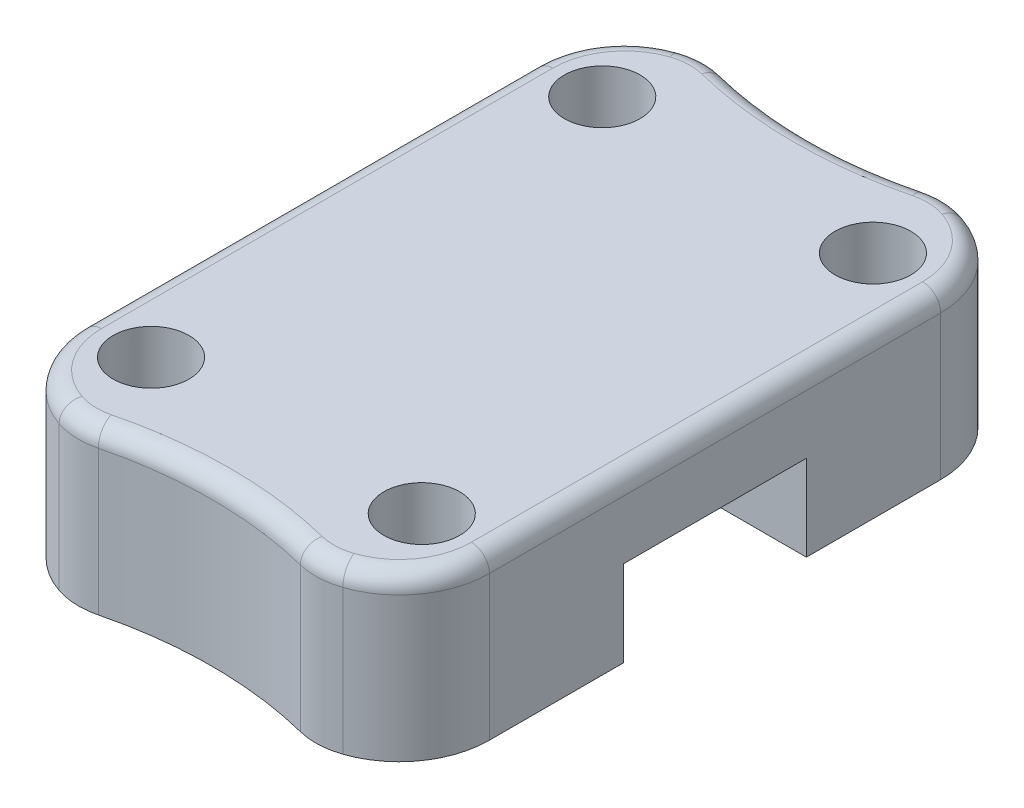
SolidWorks part; units mm, degrees
ref_plane "Спереди" through (0, 0, 0) normal (0, 0, 1) x (1, 0, 0)
ref_plane "Сверху" through (0, 0, 0) normal (0, 1, 0) x (1, 0, 0)
ref_plane "Справа" through (0, 0, 0) normal (1, 0, 0) x (0, 0, -1)
sketch "Sketch1" plane through (0, 0, 0) normal (0, 1, 0) x (1, 0, 0)
  line L1 (22.5, -35) -> (-22.5, -35)
  line L2 (22.5, -35) -> (22.5, 35)
  line L3 (22.5, 35) -> (-22.5, 35)
  line L4 (-22.5, -35) -> (-22.5, 35)
  line L5 (22.5, -35) -> (-22.5, 35) construction
  line L6 (22.5, 35) -> (-22.5, -35) construction
  point P0 (0, 0)
  dimension "D1" = 45
  dimension "D2" = 70
extrude "Boss-Extrude1" add sketch "Sketch1" along normal blind 18
sketch "Sketch2" plane through (22.5, 0, 0) normal (1, 0, 0) x (0, 0, -1)
  line L0 (0, 0) -> (0, 18) construction
  line L1 (-35, 0) -> (35, 0) construction
  line L2 (-35, 18) -> (35, 18) construction
  line L4 (10.125, 9.5) -> (-10.125, 9.5)
  line L5 (10.125, 9.5) -> (10.125, 0)
  line L6 (10.125, 0) -> (-10.125, 0)
  line L7 (-10.125, 9.5) -> (-10.125, 0)
  line L8 (10.125, 9.5) -> (-10.125, 0) construction
  line L9 (10.125, 0) -> (-10.125, 9.5) construction
  point P6 (0, 4.75)
  dimension "D1" = 20.25
  dimension "D2" = 9.5
extrude "Cut-Extrude1" cut sketch "Sketch2" against normal through all and the other way through all
sketch "Sketch3" plane through (0, 0, 0) normal (0, -1, 0) x (1, 0, 0)
  line L0 (15, -25) -> (15, 25) construction
  line L1 (-15, 25) -> (-15, -25) construction
  line L2 (-15, -25) -> (15, 25) construction
  line L3 (-22.5, -25) -> (22.5, -25) construction
  line L4 (-22.5, -35) -> (-22.5, -10.125) construction
  line L5 (22.5, -10.125) -> (22.5, -35) construction
  line L6 (-22.5, 25) -> (22.5, 25) construction
  line L7 (-22.5, 10.125) -> (-22.5, 35) construction
  line L8 (22.5, 35) -> (22.5, 10.125) construction
  line L9 (-15, 25) -> (15, -25) construction
  circle A0 centre (15, 25) radius 4.2
  circle A1 centre (15, -25) radius 4.2
  circle A2 centre (-15, -25) radius 4.2
  circle A3 centre (-15, 25) radius 4.2
  point P4 (0, 0)
  dimension "D1" = 8.4
  dimension "D2" = 30
  dimension "D3" = 50
extrude "Cut-Extrude2" cut sketch "Sketch3" against normal through all
fillet "Fillet1" radius 10 4 edges at (-22.5, 9, 35) (22.5, 9, 35) (-22.5, 9, -35) (22.5, 9, -35)
sketch "Sketch6" plane through (0, 0, 0) normal (0, -1, 0) x (1, 0, 0)
  line L0 (12.5, 35) -> (-12.5, 35)
  line L1 (12.5, -35) -> (-12.5, -35)
  arc A0 (12.5, -35) -> (-12.5, -35) centre (0, -79.2691) ccw
  arc A1 (12.5, 35) -> (-12.5, 35) centre (0, 79.2691) cw
  dimension "D1" = 46
extrude "Cut-Extrude3" cut sketch "Sketch6" against normal through all
fillet "Fillet2" radius 8 4 edges at (-12.5, 9, -35) (12.5, 9, -35) (12.5, 9, 35) (-12.5, 9, 35)
fillet "Fillet4" radius 2 12 edges at (-20.631, 18, -30.8212) (-13.4734, 18, -34.8865) (0, 18, -33.2691) (13.4734, 18, -34.8865) (20.631, 18, -30.8212) (22.5, 18, 0) (20.631, 18, 30.8212) (13.4734, 18, 34.8865) (0, 18, 33.2691) (-13.4734, 18, 34.8865) (-20.631, 18, 30.8212) (-22.5, 18, 0)
chamfer "Chamfer1" distance 0.5 angle 70 4 edges at (-15, 0, 20.8) (15, 0, 20.8) (-15, 0, -29.2) (15, 0, -29.2)
